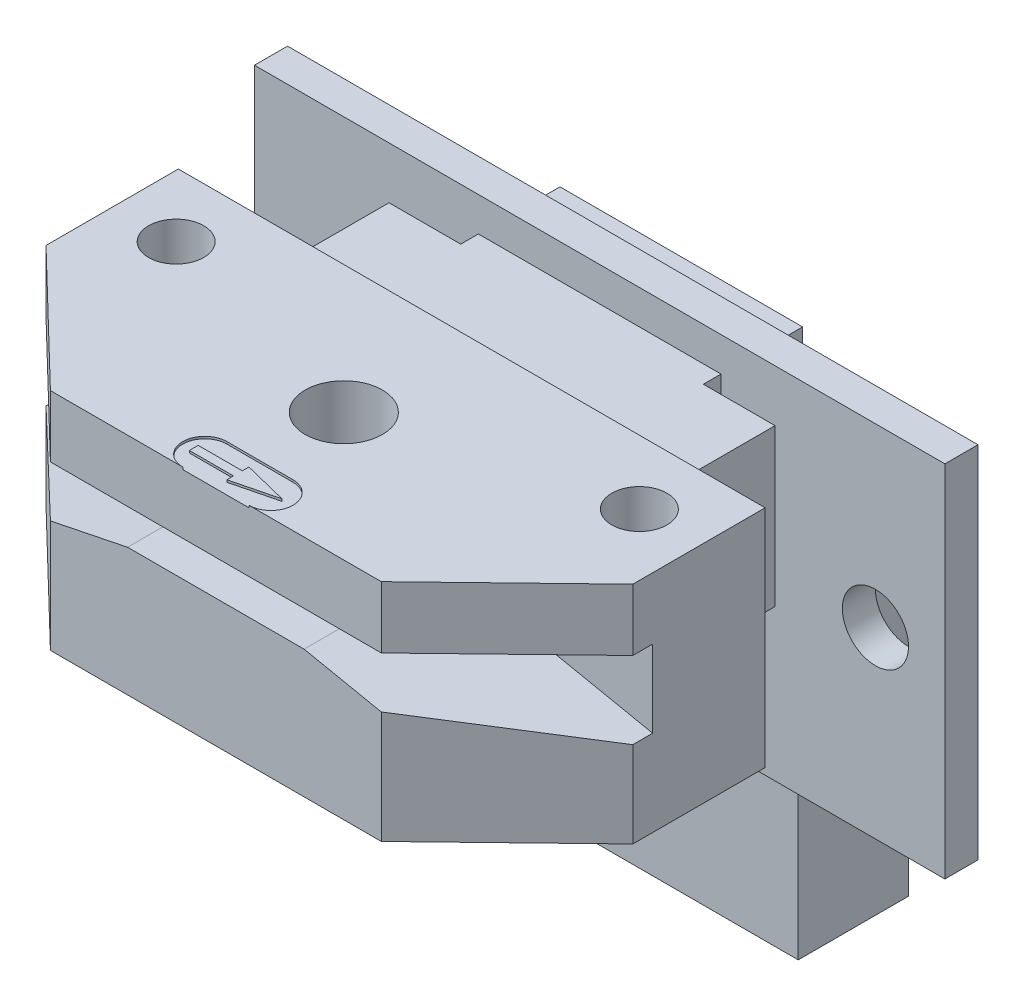
SolidWorks part; units mm, degrees
material "6063-T5"
ref_plane "Front Plane" through (0, 0, 0) normal (0, 0, 1) x (1, 0, 0)
ref_plane "Top Plane" through (0, 0, 0) normal (0, 1, 0) x (1, 0, 0)
ref_plane "Right Plane" through (0, 0, 0) normal (1, 0, 0) x (0, 0, -1)
sketch "Sketch1" plane through (0, 0, 0) normal (0, 1, 0) x (1, 0, 0)
  line L0 (-13.3, 0) -> (13.3, 0)
  line L1 (13.3, 0) -> (13.3, -6)
  line L2 (13.3, -6) -> (7.5, -11.6)
  line L3 (7.5, -11.6) -> (-7.5, -11.6)
  line L4 (-7.5, -11.6) -> (-13.3, -6)
  line L5 (-13.3, -6) -> (-13.3, 0)
  point P3 (0, -11.6)
  dimension "D1" = 26.6
  dimension "D2" = 11.6
  dimension "D3" = 6
  dimension "D4" = 15
extrude "Boss-Extrude1" add sketch "Sketch1" along normal blind 10.2
sketch "Sketch2" plane through (0, 10.2, 0) normal (0, 1, 0) x (1, 0, 0)
  line L0 (0, 0) -> (0, 2.9642) construction
  line L1 (-7.5, -11.6) -> (7.5, -11.6) construction
  line L3 (13.3, 0) -> (-13.3, 0) construction
  circle A0 centre (-10.5, -2.9) radius 1.25
  circle A1 centre (10.5, -2.9) radius 1.25
  circle A2 centre (0, -5.8) radius 1.75
  dimension "D1" = 2.5
  dimension "D5" = 3.5
  dimension "D2" = 21
  dimension "D3" = 2.9
  dimension "D4" = 5.8
extrude "Cut-Extrude1" cut sketch "Sketch2" against normal blind 10.2
sketch "Sketch3" plane through (0, 0, 11.6) normal (0, 0, 1) x (1, 0, 0)
  line L0 (-4, 5.8) -> (4, 5.8)
  line L1 (-4, 5.8) -> (-13.3, 3.9)
  line L2 (-13.3, 10.2) -> (-13.3, 0) construction
  line L3 (-13.3, 3.9) -> (-13.3, 7.4)
  line L4 (-13.3, 7.4) -> (13.3, 7.4)
  line L5 (13.3, 10.2) -> (13.3, 0) construction
  line L6 (13.3, 7.4) -> (13.3, 3.9)
  line L7 (13.3, 3.9) -> (4, 5.8)
  line L8 (-7.5, 10.2) -> (7.5, 10.2) construction
  point P2 (0, 5.8)
  dimension "D1" = 1.6
  dimension "D2" = 3.5
  dimension "D3" = 2.8
  dimension "D4" = 8
extrude "Cut-Extrude2" cut sketch "Sketch3" against normal blind 6.5
sketch "Sketch4" plane through (0, 0, 5.1) normal (0, 0, 1) x (1, 0, 0)
  line L0 (7.5, 7.4) -> (-7.5, 7.4) construction
  line L1 (-4.5, 5.8) -> (4.5, 5.8)
  line L2 (-4.5, 5.8) -> (-4.5, 7.4)
  line L3 (-4.5, 7.4) -> (4.5, 7.4)
  line L4 (4.5, 5.8) -> (4.5, 7.4)
  line L5 (-4, 5.8) -> (4, 5.8) construction
  point P7 (0, 5.8)
  dimension "D1" = 9
extrude "Cut-Extrude3" cut sketch "Sketch4" against normal blind 2.5
sketch "Sketch5" plane through (0, 10.2, 0) normal (0, 1, 0) x (1, 0, 0)
  line L0 (-1.5, -10.6) -> (1.5, -10.6) construction
  line L1 (-1.5, -9.6) -> (1.5, -9.6)
  line L2 (-1.5, -11.6) -> (1.5, -11.6)
  line L3 (-7.5, -11.6) -> (7.5, -11.6) construction
  arc A0 (-1.5, -9.6) -> (-1.5, -11.6) centre (-1.5, -10.6) ccw
  arc A1 (1.5, -11.6) -> (1.5, -9.6) centre (1.5, -10.6) ccw
  point P2 (0, -10.6)
  dimension "D1" = 2
  dimension "D2" = 3
extrude "Cut-Extrude4" cut sketch "Sketch5" against normal blind 0.1
sketch "Sketch6" plane through (0, 10.1, 0) normal (0, 1, 0) x (1, 0, 0)
  line L0 (0, -10.4) -> (0, -10.1)
  line L1 (-2, -10.8) -> (0, -10.8)
  line L2 (-2, -10.8) -> (-2, -10.4)
  line L3 (-2, -10.4) -> (0, -10.4)
  line L4 (-1.5, -11.6) -> (1.5, -11.6) construction
  line L5 (0, -10.1) -> (2, -10.6)
  line L6 (2, -10.6) -> (0, -11.1)
  line L7 (0, -11.1) -> (0, -10.8)
  arc A0 (1.5, -11.6) -> (1.5, -9.6) centre (1.5, -10.6) ccw construction
  point P4 (-2, -10.6)
  point P8 (2.5, -10.6)
  point P9 (0, -11.6)
  dimension "D1" = 0.4
  dimension "D2" = 2
  dimension "D3" = 2
  dimension "D4" = 1
extrude "Boss-Extrude2" add sketch "Sketch6" along normal blind 0.1
sketch "Sketch7" plane through (0, 0, 0) normal (0, 0, -1) x (-1, 0, 0)
  line L0 (13.3, 10.2) -> (13.3, 0) construction
  line L1 (-8.75, 1.55) -> (8.75, 1.55)
  line L2 (-8.75, 1.55) -> (-8.75, 8.65)
  line L3 (-8.75, 8.65) -> (8.75, 8.65)
  line L4 (8.75, 1.55) -> (8.75, 8.65)
  line L5 (-8.75, 1.55) -> (8.75, 8.65) construction
  line L6 (-8.75, 8.65) -> (8.75, 1.55) construction
  point P0 (0, 5.1)
  point P5 (13.3, 5.1)
  dimension "D1" = 7.1
  dimension "D2" = 17.5
extrude "Boss-Extrude3" add sketch "Sketch7" along normal blind 5
sketch "Sketch8" plane through (0, 0, -5) normal (0, 0, -1) x (-1, 0, 0)
  line L0 (8.75, 8.65) -> (-8.75, 8.65) construction
  line L1 (5.5, 8.65) -> (-5.5, 8.65)
  line L2 (5.5, 8.65) -> (5.5, 7.65)
  line L3 (5.5, 7.65) -> (-5.5, 7.65)
  line L4 (-5.5, 8.65) -> (-5.5, 7.65)
  line L5 (-8.75, 1.55) -> (8.75, 1.55) construction
  point P6 (0, 8.65)
  point P7 (0, 1.55)
  dimension "D1" = 11
  dimension "D2" = 1
extrude "Boss-Extrude4" add sketch "Sketch8" along normal blind 0.8
sketch "Sketch10" plane through (0, 0, -5.8) normal (0, 0, -1) x (-1, 0, 0)
  line L0 (13.3, 10.2) -> (13.3, 0) construction
  line L1 (-15.65, -6.1) -> (15.65, -6.1)
  line L2 (-15.65, -6.1) -> (-15.65, 10.2)
  line L3 (-15.65, 10.2) -> (15.65, 10.2)
  line L4 (15.65, -6.1) -> (15.65, 10.2)
  line L5 (-15.65, -6.1) -> (15.65, 10.2) construction
  line L6 (-15.65, 10.2) -> (15.65, -6.1) construction
  line L7 (-13.3, 10.2) -> (13.3, 10.2) construction
  point P0 (0, 2.05)
  point P5 (13.3, 5.1)
  point P11 (0, 0)
  dimension "D1" = 31.3
  dimension "D2" = 16.3
  dimension "D3" = 0
extrude "Boss-Extrude5" add sketch "Sketch10" along normal blind 1.5
sketch "Sketch11" plane through (0, 0, -7.3) normal (0, 0, -1) x (-1, 0, 0)
  line L0 (0, 0) -> (0, 7.2119) construction
  line L1 (15.65, 10.2) -> (-15.65, 10.2) construction
  circle A0 centre (-12.5, 2.2) radius 1.5
  circle A1 centre (12.5, 2.2) radius 1.5
  dimension "D1" = 3
  dimension "D2" = 8
  dimension "D3" = 25
extrude "Cut-Extrude5" cut sketch "Sketch11" against normal blind 1.5
sketch "Sketch13" plane through (0, 0, -7.3) normal (0, 0, -1) x (-1, 0, 0)
  line L0 (5.5, 8.65) -> (-5.5, 8.65) construction
  line L1 (-5.5, 7.65) -> (5.5, 7.65)
  line L2 (-5.5, 7.65) -> (-5.5, 8.65)
  line L3 (-5.5, 8.65) -> (5.5, 8.65)
  line L4 (5.5, 7.65) -> (5.5, 8.65)
  line L5 (-5.5, 8.65) -> (-5.5, 7.65) construction
  line L6 (-5.5, 7.65) -> (5.5, 7.65) construction
  line L7 (5.5, 7.65) -> (5.5, 8.65) construction
extrude "Boss-Extrude6" add sketch "Sketch13" along normal blind 2.2
sketch "Sketch14" plane through (0, 0, -7.3) normal (0, 0, -1) x (-1, 0, 0)
  line L0 (-15.65, -6.1) -> (15.65, -6.1) construction
  line L1 (-7.5, -0.1) -> (7.5, -0.1)
  line L2 (-7.5, -0.1) -> (-7.5, -14.1)
  line L3 (-7.5, -14.1) -> (7.5, -14.1)
  line L4 (7.5, -0.1) -> (7.5, -14.1)
  dimension "D1" = 14
  dimension "D2" = 6
  dimension "D3" = 7.5
  dimension "D4" = 15
extrude "Boss-Extrude7" add sketch "Sketch14" along normal blind 5 separate body
